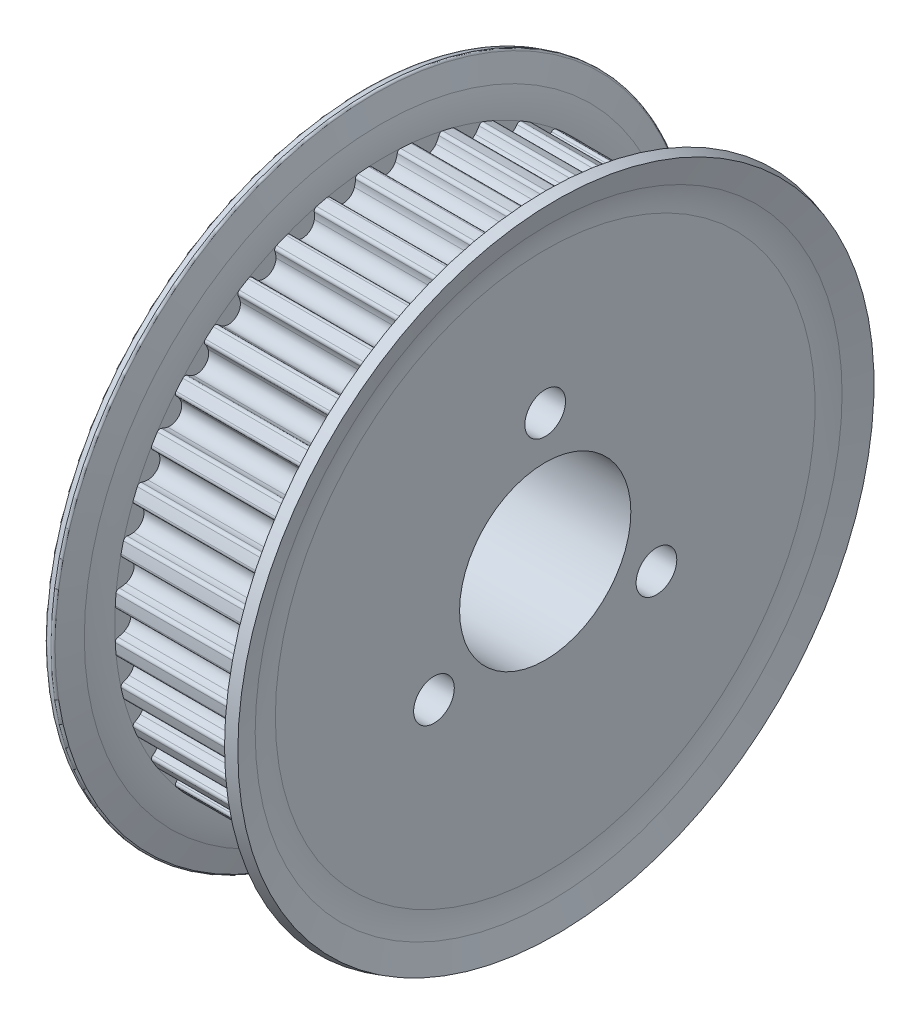
SolidWorks part; units mm, degrees
ref_plane "Front" through (0, 0, 0) normal (0, 0, 1) x (1, 0, 0)
ref_plane "Top" through (0, 0, 0) normal (0, 1, 0) x (1, 0, 0)
ref_plane "Right" through (0, 0, 0) normal (1, 0, 0) x (0, 0, -1)
sketch "Sketch1" plane through (0, 0, 0) normal (1, 0, 0) x (0, 0, -1)
  circle A0 centre (0, 0) radius 4
  circle A1 centre (0, 0) radius 12.6054
  dimension "D1" = 8
  dimension "D2" = 25.2108
extrude "Boss-Extrude1" add sketch "Sketch1" along normal mid plane 7
sketch "Sketch2" plane through (0, 0, 0) normal (1, 0, 0) x (0, 0, -1)
  line L0 (0, 0) -> (0, 12.6054) construction
  circle A0 centre (0, 0) radius 12.6054 construction
  arc A1 (0.7469, 12.5832) -> (-0.7469, 12.5832) centre (0, 0) ccw
  arc A2 (-0.7469, 12.5832) -> (-0.5896, 12.4551) centre (-0.738, 12.4335) cw
  arc A3 (-0.5896, 12.4551) -> (-0.4989, 12.1608) centre (0.4, 12.599) ccw
  arc A4 (-0.4989, 12.1608) -> (0.4989, 12.1608) centre (0, 12.404) ccw
  arc A5 (0.7469, 12.5832) -> (0.5896, 12.4551) centre (0.738, 12.4335) ccw
  arc A6 (0.5896, 12.4551) -> (0.4989, 12.1608) centre (-0.4, 12.599) cw
  dimension "D1" = 0.15
  dimension "D2" = 1
  dimension "D3" = 0.555
  dimension "D4" = 0.4
extrude "Cut-Extrude1" cut sketch "Sketch2" against normal mid plane 7
pattern_circular "CirPattern1" count 40 over 360 about axis through (0, 0, 0) along (1, 0, 0) of "Cut-Extrude1"
sketch "Sketch3" plane through (0, 0, 0) normal (0, 0, 1) x (1, 0, 0)
  line L0 (0, 12.6054) -> (0, 0) construction
  line L1 (0, 0) -> (5.1043, 0) construction
  line L2 (-3.5, 4) -> (-3.5, 12.6054)
  line L3 (-3.6801, 13.8493) -> (-4.0205, 15)
  line L4 (-4.0205, 15) -> (-4.5, 14.8582)
  line L5 (-4.5, 14.8582) -> (-4.1596, 13.7075)
  line L7 (-4, 12.6054) -> (-4, 5)
  line L8 (-4, 5) -> (-4.25, 5)
  line L9 (-4.25, 5) -> (-4.25, 4.5)
  line L10 (-4.25, 4.5) -> (-4.5, 4.5)
  line L11 (-4.5, 4.5) -> (-4.5, 4)
  line L12 (-4.5, 4) -> (-3.5, 4)
  line L16 (4.5, 4.5) -> (4.5, 4)
  line L17 (4.25, 4.5) -> (4.5, 4.5)
  line L18 (4.25, 5) -> (4.25, 4.5)
  line L19 (4, 5) -> (4.25, 5)
  line L20 (4, 12.6054) -> (4, 5)
  line L21 (4.5, 14.8582) -> (4.1596, 13.7075)
  line L22 (4.0205, 15) -> (4.5, 14.8582)
  line L23 (3.6801, 13.8493) -> (4.0205, 15)
  line L24 (3.5, 4) -> (3.5, 12.6054)
  line L25 (4.5, 4) -> (3.5, 4)
  arc A0 (-3.5, 12.6054) -> (-3.6801, 13.8493) centre (-7.885, 12.6054) ccw
  arc A1 (-4.1596, 13.7075) -> (-4, 12.6054) centre (-7.885, 12.6054) cw
  arc A2 (4.1596, 13.7075) -> (4, 12.6054) centre (7.885, 12.6054) ccw
  arc A3 (3.5, 12.6054) -> (3.6801, 13.8493) centre (7.885, 12.6054) cw
  dimension "D1" = 9
  dimension "D2" = 30
  dimension "D3" = 0.5
  dimension "D4" = 1.2
  dimension "D5" = 1
  dimension "D6" = 10
revolve "Revolve1" add sketch "Sketch3" angle 360 about L1
sketch "Sketch4" plane through (0, 0, 0) normal (0, 0, 1) x (1, 0, 0)
  line L0 (0, 7.2927) -> (0, 0) construction
  line L1 (0, 0) -> (12.9063, 0) construction
  line L2 (4.0205, 15) -> (4.0205, 0) construction
  line L4 (0, 0) -> (5.1043, 0) construction
  line L5 (4.0205, 8) -> (12.5, 8)
  line L6 (12.5, 8) -> (12.5, 4)
  line L7 (12.5, 4) -> (3.8109, 4)
  line L8 (3.8109, 4) -> (4.0205, 8)
  line L9 (4.5, 4) -> (3.5, 4) construction
  line L10 (-4.5, 4.5) -> (-4.5, 4) construction
  dimension "D1" = 16
  dimension "D2" = 17
  dimension "D3" = 93
revolve "Revolve2" add sketch "Sketch4" angle 360 about L1
fillet "Fillet1" radius 0.1 6 edges at (-4, 0, 5) (-4.25, 0, 5) (-4.25, 0, 4.5) (12.5, 0, 8) (-4.0205, 0, 15) (-4.5, 0, 14.8582)
sketch "Sketch5" plane through (0, 0, 0) normal (0, 0, 1) x (1, 0, 0)
  line L0 (4.0205, 0) -> (12.5, 0) construction
  line L1 (4.0205, 15) -> (4.0205, 0) construction
  line L2 (12.5, 8) -> (12.5, 4) construction
hole_wizard "M4 Tapped Hole1" positions "Sketch7" profile "Sketch6" tap size "M4" standard "ISO"
sketch "Sketch7" plane through (0, 0, 0) normal (0, 0, 1) x (1, 0, 0)
  line L0 (4.0205, 0) -> (12.5, 0) construction
  point P0 (8.2603, 0)
sketch "Sketch6" plane through (8.2603, 0, 0) normal (1, 0, 0) x (0, 1, 0)
  line L0 (0, 0) -> (0, 8)
  line L1 (0, 8) -> (1.65, 8)
  line L2 (1.65, 8) -> (1.65, 0)
  line L5 (1.65, 0) -> (0, 0)
  line L11 (0, -6.35) -> (0, 107.95) construction
  dimension "Thru Tap Drill Dia." = 3.3
  dimension "Thru Tap Drill Depth" = 8
cosmetic thread "Hole Thread1" parameters "D2"=4
sketch "Sketch9" plane through (4, 0, 0) normal (1, 0, 0) x (0, 0, -1)
  circle A0 centre (0, 0) radius 8 construction
  circle A1 centre (0, 0) radius 8
extrude "Cut-Extrude2" cut sketch "Sketch9" along normal through all
sketch "Sketch10" plane through (4, 0, 0) normal (1, 0, 0) x (0, 0, -1)
  line L0 (-5.1962, -3) -> (5.1962, -3) construction
  line L1 (5.1962, -3) -> (0, 6) construction
  line L2 (0, 6) -> (-5.1962, -3) construction
  circle A0 centre (0, 0) radius 6 construction
  circle A1 centre (0, 6) radius 0.95
  circle A2 centre (5.1962, -3) radius 0.95
  circle A3 centre (-5.1962, -3) radius 0.95
  dimension "D1" = 12
  dimension "D2" = 1.9
extrude "Cut-Extrude3" cut sketch "Sketch10" against normal through all
equation "\"Pitch\"= 2"
equation "\"Outside Fillet\"= .15"
equation "\"Side Radius\"= 1"
equation "\"Bottom Radius\"= .555"
equation "\"Tooth height\"= .75"
equation "\"Teeth_Count\"=40"
equation "\"Side radius offset\"= .4"
equation "\"Effective radius offset\"= 0.254"
equation "\"Belt width\"= 6"
equation "\"Pulley extra width\"= 1"
equation "\"Rim_Diameter\"=30"
equation "\"Rim_Width\"= 1"
equation "\"Pulley_Width\"= \"Belt width\" + \"Pulley extra width\" + 2 * \"Rim_Width\""
equation "\"Overall Width\"=17"
equation "\"Fastening Diameter\"=16"
equation "\"D2@Sketch1\"=\"Pitch\"*\"Teeth_Count\"/pi - \"Effective radius offset\""
equation "\"D1@Boss-Extrude1\"=\"Belt width\"+\"Pulley extra width\""
equation "\"D1@Sketch2\"=\"Outside Fillet\""
equation "\"D2@Sketch2\"=\"Side Radius\""
equation "\"D3@Sketch2\"=\"Bottom Radius\""
equation "\"D4@Sketch2\"=\"Side radius offset\""
equation "\"D1@Cut-Extrude1\"=\"Belt width\"+\"Pulley extra width\""
equation "\"D1@CirPattern1\"=\"Teeth_Count\""
equation "\"D2@Sketch3\"=\"Rim_Diameter\""
equation "\"D1@Sketch4\"=\"Fastening Diameter\""
equation "\"D2@Sketch4\"=\"Overall Width\""
